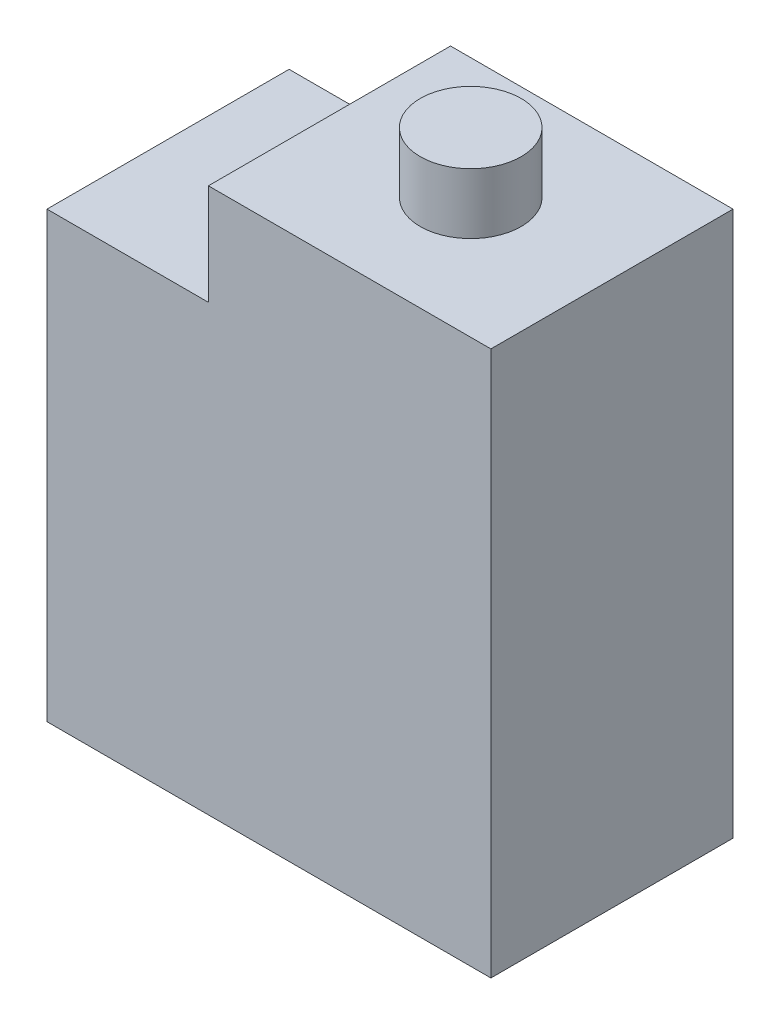
SolidWorks part; units mm, degrees
material "servomotor"
ref_plane "Alzado" through (0, 0, 0) normal (0, 0, 1) x (1, 0, 0)
ref_plane "Planta" through (0, 0, 0) normal (0, 1, 0) x (1, 0, 0)
ref_plane "Vista lateral" through (0, 0, 0) normal (1, 0, 0) x (0, 0, -1)
sketch "Croquis1" plane through (0, 0, 0) normal (0, 1, 0) x (1, 0, 0)
  line L1 (-11, -6) -> (11, -6)
  line L2 (-11, -6) -> (-11, 6)
  line L3 (-11, 6) -> (11, 6)
  line L4 (11, -6) -> (11, 6)
  line L5 (-11, -6) -> (11, 6) construction
  line L6 (-11, 6) -> (11, -6) construction
  point P0 (0, 0)
  dimension "D1" = 12
  dimension "D2" = 22
extrude "Saliente-Extruir1" add sketch "Croquis1" along normal blind 22
sketch "Croquis2" plane through (0, 22, 0) normal (0, 1, 0) x (1, 0, 0)
  line L1 (11, 6) -> (-3, 6)
  line L2 (11, 6) -> (11, -6)
  line L3 (11, -6) -> (-3, -6)
  line L4 (-3, 6) -> (-3, -6)
  line L5 (-11, -6) -> (11, -6) construction
  dimension "D1" = 12
  dimension "D2" = 14
extrude "Saliente-Extruir2" add sketch "Croquis2" along normal blind 5
sketch "Croquis3" plane through (0, 27, 0) normal (0, 1, 0) x (1, 0, 0)
  line L0 (-3, -6) -> (11, 6) construction
  line L1 (11, -6) -> (-3, 6) construction
  circle A0 centre (4, 0) radius 2.5
  dimension "D1" = 5
extrude "Saliente-Extruir3" add sketch "Croquis3" along normal blind 3
